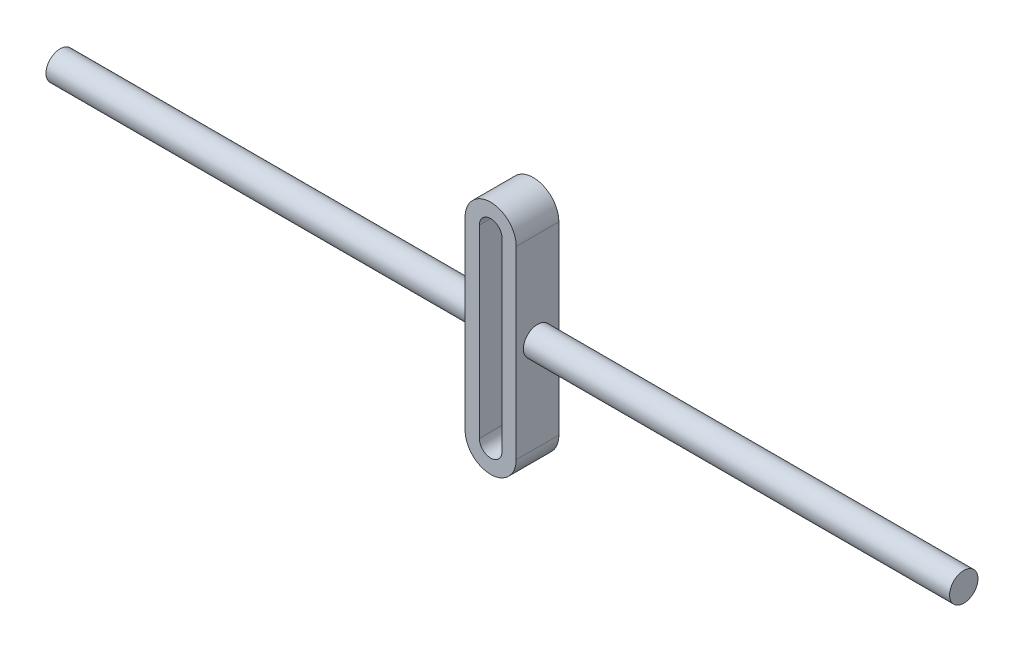
SolidWorks part; units mm, degrees
ref_plane "Front Plane" through (0, 0, 0) normal (0, 0, 1) x (1, 0, 0)
ref_plane "Top Plane" through (0, 0, 0) normal (0, 1, 0) x (1, 0, 0)
ref_plane "Right Plane" through (0, 0, 0) normal (1, 0, 0) x (0, 0, -1)
sketch "Sketch1" plane through (0, 0, 0) normal (0, 0, 1) x (1, 0, 0)
  line L0 (0, 0) -> (0, 65) construction
  line L1 (-4, 0) -> (-4, 65)
  line L2 (4, 0) -> (4, 65)
  line L3 (-9, 0) -> (-9, 65)
  line L4 (9, 0) -> (9, 65)
  arc A0 (-4, 0) -> (4, 0) centre (0, 0) ccw
  arc A1 (4, 65) -> (-4, 65) centre (0, 65) ccw
  arc A2 (9, 65) -> (-9, 65) centre (0, 65) ccw
  arc A3 (-9, 0) -> (9, 0) centre (0, 0) ccw
  point P2 (0, 32.5)
  dimension "D1" = 65
  dimension "D2" = 8
  dimension "D3" = 5
extrude "Boss-Extrude1" add sketch "Sketch1" along normal blind 15
sketch "Sketch2" plane through (9, 0, 0) normal (1, 0, 0) x (0, 0, -1)
  line L0 (-7.5, 65) -> (-7.5, 0) construction
  line L1 (-15, 65) -> (0, 65) construction
  line L2 (-15, 0) -> (0, 0) construction
  circle A0 centre (-7.5, 32.5) radius 5
  dimension "D1" = 10
extrude "Boss-Extrude2" add sketch "Sketch2" along normal blind 150
mirror "Mirror1" about plane through (0, 0, 0) normal (1, 0, 0) of "Boss-Extrude2"
